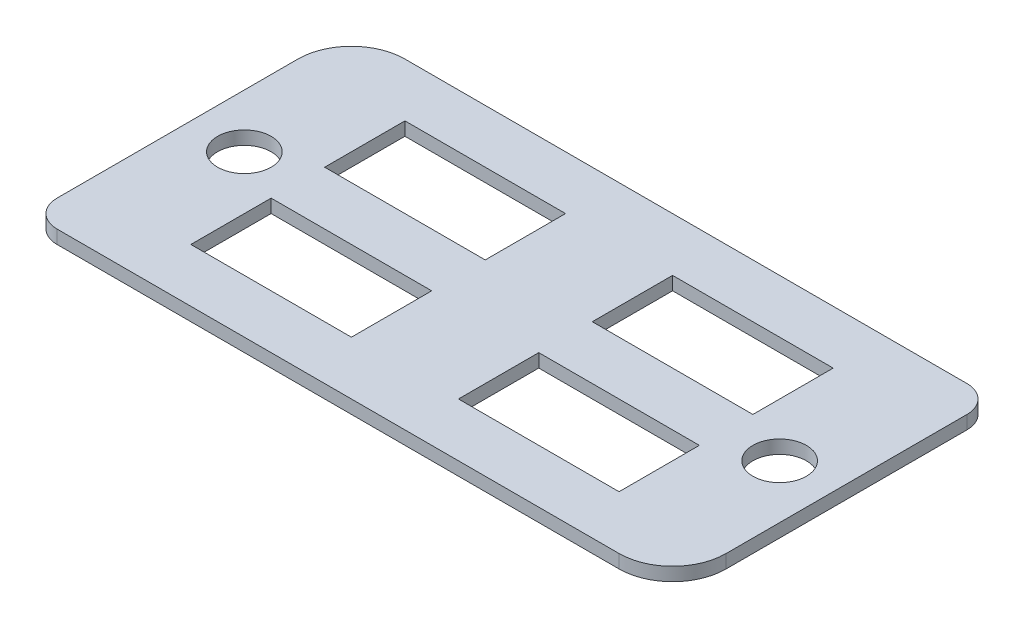
SolidWorks part; units mm, degrees
ref_plane "Front Plane" through (0, 0, 0) normal (0, 0, 1) x (1, 0, 0)
ref_plane "Top Plane" through (0, 0, 0) normal (0, 1, 0) x (1, 0, 0)
ref_plane "Right Plane" through (0, 0, 0) normal (1, 0, 0) x (0, 0, -1)
sketch "Sketch1" plane through (0, 0, 0) normal (0, 1, 0) x (1, 0, 0)
  line L1 (0, 0) -> (304.8, 0)
  line L2 (0, 0) -> (0, 152.4)
  line L3 (0, 152.4) -> (304.8, 152.4)
  line L4 (304.8, 0) -> (304.8, 152.4)
  line L5 (50.8, 127) -> (127, 127)
  line L6 (50.8, 127) -> (50.8, 88.9)
  line L7 (50.8, 88.9) -> (127, 88.9)
  line L8 (127, 127) -> (127, 88.9)
  line L9 (50.8, 63.5) -> (127, 63.5)
  line L10 (50.8, 63.5) -> (50.8, 25.4)
  line L11 (50.8, 25.4) -> (127, 25.4)
  line L12 (127, 63.5) -> (127, 25.4)
  line L13 (177.8, 127) -> (254, 127)
  line L14 (177.8, 127) -> (177.8, 88.9)
  line L15 (177.8, 88.9) -> (254, 88.9)
  line L16 (254, 127) -> (254, 88.9)
  line L17 (177.8, 63.5) -> (254, 63.5)
  line L18 (177.8, 63.5) -> (177.8, 25.4)
  line L19 (177.8, 25.4) -> (254, 25.4)
  line L20 (254, 63.5) -> (254, 25.4)
  circle A0 centre (25.4, 76.2) radius 12.7
  circle A1 centre (279.4, 76.2) radius 12.7
  dimension "D7" = 12.7
  dimension "D11" = 25.4
  dimension "D1" = 304.8
  dimension "D2" = 152.4
  dimension "D3" = 76.2
  dimension "D4" = 38.1
  dimension "D5" = 25.4
  dimension "D6" = 50.8
  dimension "D8" = 25.4
  dimension "D9" = 38.1
  dimension "D10" = 25.4
  dimension "D12" = 76.2
  dimension "D13" = 38.1
  dimension "D14" = 50.8
  dimension "D15" = 50.8
  dimension "D16" = 76.2
  dimension "D17" = 38.1
extrude "Boss-Extrude1" add sketch "Sketch1" along normal blind 6.35
fillet "Fillet2" radius 25.4 2 edges at (304.8, 3.175, 0) (0, 3.175, -152.4)
fillet "Fillet3" radius 12.7 2 edges at (304.8, 3.175, -152.4) (0, 3.175, 0)
